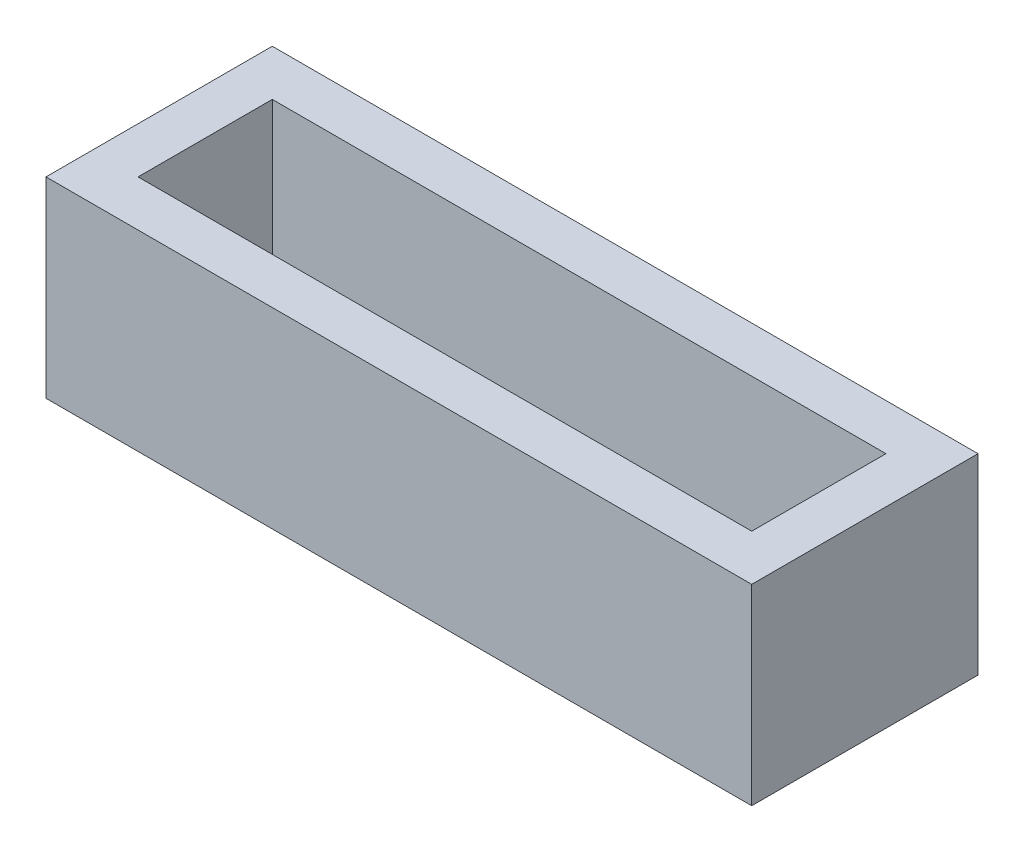
SolidWorks part; units mm, degrees
ref_plane "Front Plane" through (0, 0, 0) normal (0, 0, 1) x (1, 0, 0)
ref_plane "Top Plane" through (0, 0, 0) normal (0, 1, 0) x (1, 0, 0)
ref_plane "Right Plane" through (0, 0, 0) normal (1, 0, 0) x (0, 0, -1)
sketch "Sketch1" plane through (0, 0, 0) normal (0, 1, 0) x (1, 0, 0)
  line L0 (-9.2, 2.95) -> (-9.2, -2.95)
  line L1 (-8, 1.75) -> (8, 1.75)
  line L2 (-8, 1.75) -> (-8, -1.75)
  line L3 (-8, -1.75) -> (8, -1.75)
  line L4 (8, 1.75) -> (8, -1.75)
  line L5 (-8, 1.75) -> (8, -1.75) construction
  line L6 (-8, -1.75) -> (8, 1.75) construction
  line L7 (-9.2, -2.95) -> (9.2, -2.95)
  line L8 (9.2, 2.95) -> (9.2, -2.95)
  line L9 (-9.2, 2.95) -> (9.2, 2.95)
  point P0 (0, 0)
  dimension "D1" = 3.5
  dimension "D2" = 16
  dimension "D3" = 1.2
extrude "Boss-Extrude1" add sketch "Sketch1" along normal blind 5
